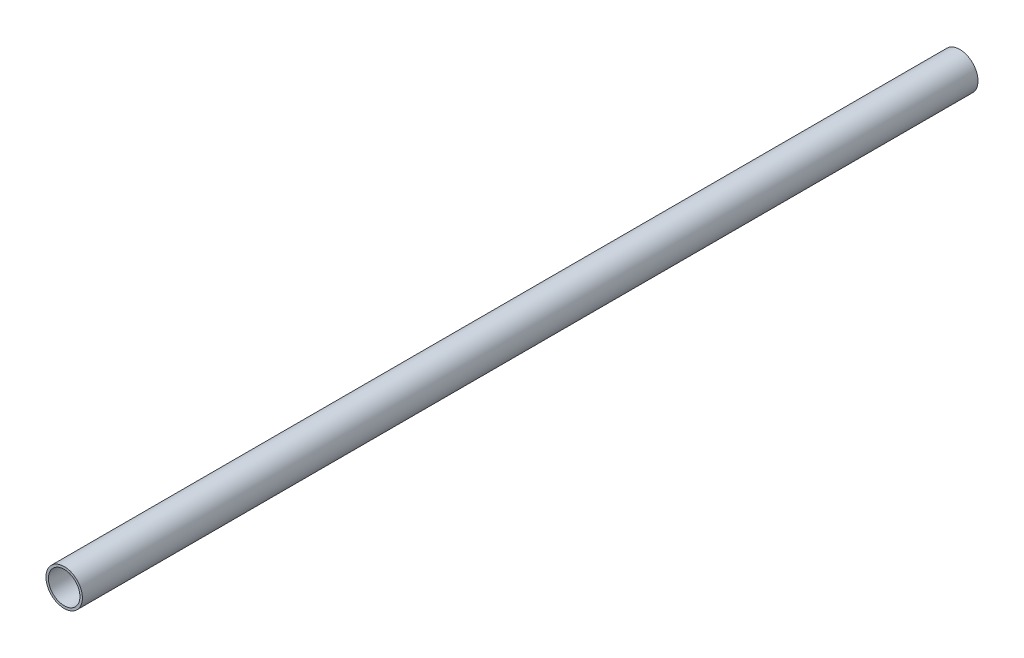
SolidWorks part; units mm, degrees
ref_plane "Alzado" through (0, 0, 0) normal (0, 0, 1) x (1, 0, 0)
ref_plane "Planta" through (0, 0, 0) normal (0, 1, 0) x (1, 0, 0)
ref_plane "Vista lateral" through (0, 0, 0) normal (1, 0, 0) x (0, 0, -1)
sketch "Croquis1" plane through (0, 0, 0) normal (0, 0, 1) x (1, 0, 0)
  circle A0 centre (0, 0) radius 6.35
  dimension "D1" = 12.7
extrude "Saliente-Extruir1" add sketch "Croquis1" along normal blind 312.3
sketch "Croquis2" plane through (0, 0, 312.3) normal (0, 0, 1) x (1, 0, 0)
  circle A0 centre (0, 0) radius 5.5
extrude "Cortar-Extruir1" cut sketch "Croquis2" against normal blind 352.3 and the other way blind 102 contours A0
